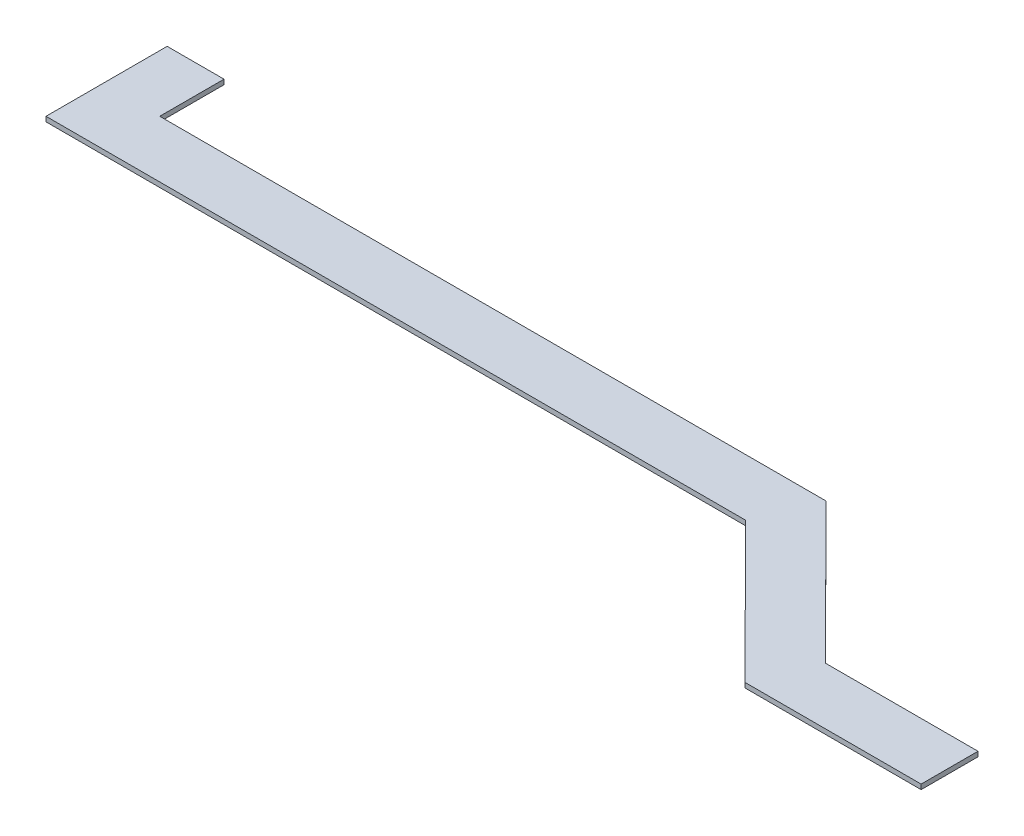
SolidWorks part; units mm, degrees
ref_plane "Front Plane" through (0, 0, 0) normal (0, 0, 1) x (1, 0, 0)
ref_plane "Top Plane" through (0, 0, 0) normal (0, 1, 0) x (1, 0, 0)
ref_plane "Right Plane" through (0, 0, 0) normal (1, 0, 0) x (0, 0, -1)
sketch "Sketch1" plane through (0, 0, 0) normal (0, 1, 0) x (1, 0, 0)
  line L0 (0, 0) -> (0, -7.5)
  line L1 (0, -7.5) -> (43.3004, -7.5)
  line L2 (0, 0) -> (3.52, 0)
  line L3 (3.52, 0) -> (3.52, -3.98)
  line L4 (3.52, -3.98) -> (44.7617, -3.98)
  line L5 (43.3004, -7.5) -> (51.9868, -16.2136)
  line L6 (44.7617, -3.98) -> (53.4481, -12.6936)
  line L7 (53.4481, -12.6936) -> (62.8868, -12.6936)
  line L8 (51.9868, -16.2136) -> (62.8868, -16.2136)
  line L9 (62.8868, -12.6936) -> (62.8868, -16.2136)
  dimension "D1" = 3.52
  dimension "D2" = 7.5
  dimension "D3" = 12.3037
  dimension "D4" = 3.52
  dimension "D5" = 3.52
  dimension "D6" = 43.3004
  dimension "D7" = 3.52
  dimension "D8" = 10.9
  dimension "D9" = 8.6864
  dimension "D10" = 9.4387
extrude "Boss-Extrude1" add sketch "Sketch1" along normal blind 0.3
